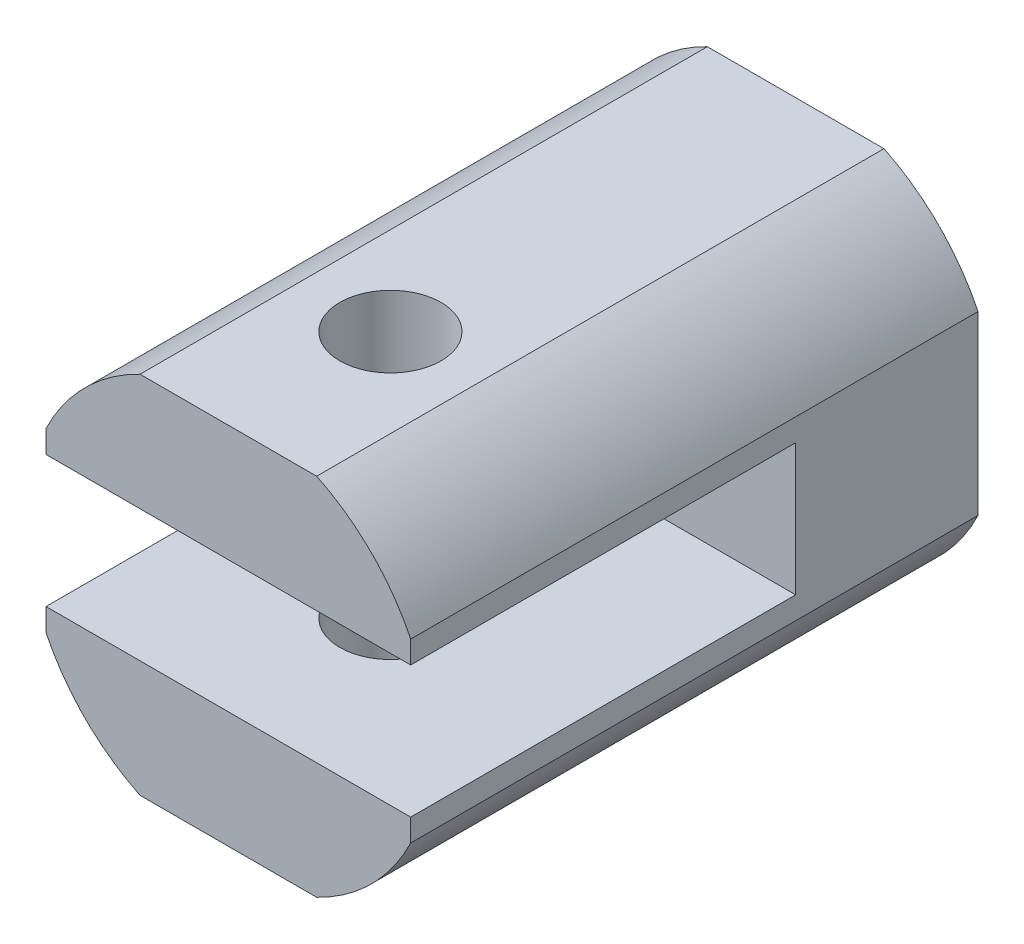
SolidWorks part; units mm, degrees
ref_plane "Front Plane" through (0, 0, 0) normal (0, 0, 1) x (1, 0, 0)
ref_plane "Top Plane" through (0, 0, 0) normal (0, 1, 0) x (1, 0, 0)
ref_plane "Right Plane" through (0, 0, 0) normal (1, 0, 0) x (0, 0, -1)
sketch "Sketch1" plane through (0, 0, 0) normal (0, 0, 1) x (1, 0, 0)
  line L0 (-59.7969, 0) -> (65.1213, 0) construction
  line L1 (0, 64.5069) -> (0, -59.1825) construction
  line L3 (-4.3589, 9) -> (4.3589, 9)
  line L4 (-9, 4.3589) -> (-9, -4.3589)
  line L5 (-4.3589, -9) -> (4.3589, -9)
  line L6 (9, 4.3589) -> (9, -4.3589)
  arc A0 (-9, -4.3589) -> (-4.3589, -9) centre (0, 0) ccw
  arc A1 (4.3589, -9) -> (9, -4.3589) centre (0, 0) ccw
  arc A2 (9, 4.3589) -> (4.3589, 9) centre (0, 0) ccw
  arc A3 (-4.3589, 9) -> (-9, 4.3589) centre (0, 0) ccw
  point P5 (0, 0)
extrude "Boss-Extrude2" add sketch "Sketch1" against normal blind 28
sketch "Sketch3" plane through (0, 0, 0) normal (0, 0, 1) x (1, 0, 0)
  line L0 (9, -4.3589) -> (9, 4.3589) construction
  line L1 (-9, 3.25) -> (9, 3.25)
  line L2 (-9, 3.25) -> (-9, -3.25)
  line L3 (-9, -3.25) -> (9, -3.25)
  line L4 (9, 3.25) -> (9, -3.25)
  line L5 (-9, 3.25) -> (9, -3.25) construction
  line L6 (-9, -3.25) -> (9, 3.25) construction
  point P0 (0, 0)
extrude "Cut-Extrude9" cut sketch "Sketch3" against normal blind 19
sketch "Sketch4" plane through (0, 0, 0) normal (0, 1, 0) x (1, 0, 0)
  line L0 (0, -13.3195) -> (0, 26.6583) construction
  line L1 (14.6857, 0) -> (-15.3996, 0) construction
  circle A0 centre (0, 8) radius 2.5
  dimension "D1" = 8
extrude "Cut-Extrude10" cut sketch "Sketch4" against normal through all both and the other way through all
